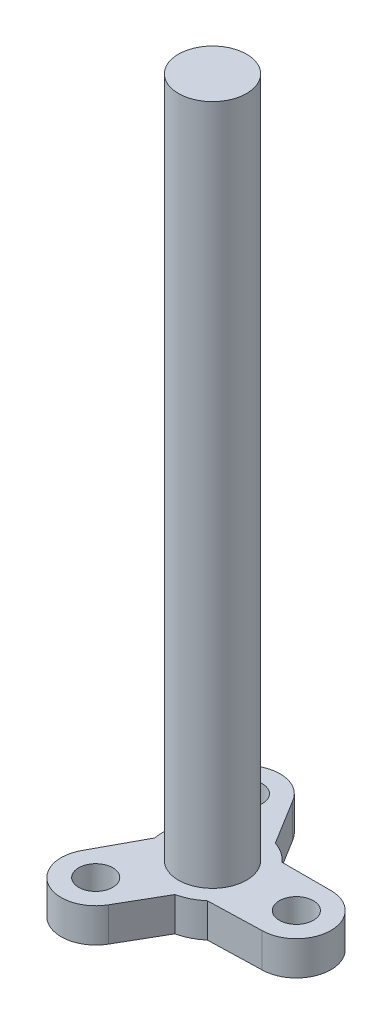
SolidWorks part; units mm, degrees
ref_plane "Front Plane" through (0, 0, 0) normal (0, 0, 1) x (1, 0, 0)
ref_plane "Top Plane" through (0, 0, 0) normal (0, 1, 0) x (1, 0, 0)
ref_plane "Right Plane" through (0, 0, 0) normal (1, 0, 0) x (0, 0, -1)
sketch "Sketch1" plane through (0, 0, 0) normal (0, 1, 0) x (1, 0, 0)
  circle A0 centre (0, 0) radius 2
extrude "Boss-Extrude1" add sketch "Sketch1" along normal blind 40
sketch "Sketch2" plane through (0, 0, 0) normal (0, -1, 0) x (1, 0, 0)
  line L0 (0, 0) -> (4.9994, 0.0759) construction
  line L1 (4.9994, -1.953) -> (2.1397, -1.953)
  line L2 (4.9994, 2.1049) -> (1.8916, 2.1942)
  line L3 (-4.1911, -3.3531) -> (-2.7613, -0.8766)
  line L4 (-0.6768, -5.3821) -> (0.9544, -2.7353)
  line L5 (-0.8083, 5.3061) -> (0.6215, 2.8296)
  line L6 (-4.3226, 3.2772) -> (-2.8461, 0.5411)
  circle A5 centre (4.9994, 0.0759) radius 2.029
  circle A6 centre (4.9994, 0.0759) radius 1
  circle A12 centre (0, 0) radius 2.897
  circle A13 centre (0, 0) radius 2.897
  circle A14 centre (-2.434, -4.3676) radius 2.029
  circle A15 centre (-2.434, -4.3676) radius 1
  circle A16 centre (0, 0) radius 2.897
  circle A17 centre (-2.5655, 4.2917) radius 2.029
  circle A18 centre (-2.5655, 4.2917) radius 1
  dimension "D1" = 3
extrude "Boss-Extrude2" add sketch "Sketch2" along normal blind 2 separate body
